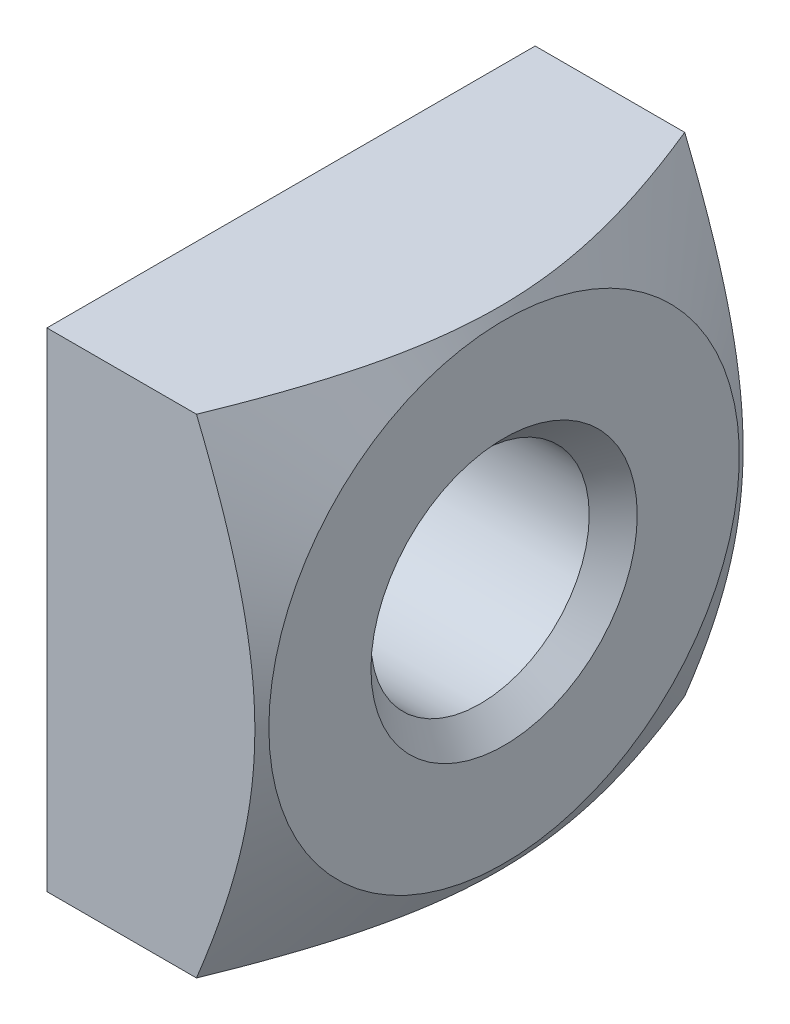
SolidWorks part; units mm, degrees
ref_plane "Front Plane" through (0, 0, 0) normal (0, 0, 1) x (1, 0, 0)
ref_plane "Top Plane" through (0, 0, 0) normal (0, 1, 0) x (1, 0, 0)
ref_plane "Right Plane" through (0, 0, 0) normal (1, 0, 0) x (0, 0, -1)
ref_plane "Plane1" through (0, 0, 0) normal (0, 0, 1) x (1, 0, 0)
sketch "Sketch1" plane through (0, 0, 0) normal (0, 0, 1) x (1, 0, 0)
  line L0 (0, 0) -> (0, 3.9)
  line L1 (0, 3.9) -> (1.6783, 3.9)
  line L2 (1.6783, 3.9) -> (2.4, 2.65)
  line L3 (2.4, 2.65) -> (2.4, 0)
  line L4 (2.4, 0) -> (0, 0)
  line L5 (2.4, 0) -> (0, 0) construction
revolve "Revolve1" add sketch "Sketch1" angle 360 about L5
ref_plane "Plane2" through (0, 0, 0) normal (1, 0, 0) x (0, 0, -1)
sketch "Sketch2" plane through (0, 0, 0) normal (1, 0, 0) x (0, 0, -1)
  line L0 (-2.75, 2.75) -> (-2.75, -2.75)
  line L1 (-2.75, -2.75) -> (2.75, -2.75)
  line L2 (2.75, -2.75) -> (2.75, 2.75)
  line L3 (2.75, 2.75) -> (-2.75, 2.75)
  circle A0 centre (0, 0) radius 5
extrude "Cut-Extrude1" cut sketch "Sketch2" along normal blind 6
ref_plane "Plane3" through (0, 0, 0) normal (0, 0, 1) x (1, 0, 0)
sketch "Sketch3" plane through (0, 0, 0) normal (0, 0, 1) x (1, 0, 0)
  line L0 (0, 0) -> (0, 1.5)
  line L1 (0, 1.5) -> (0.2705, 1.2295)
  line L2 (0.2705, 1.2295) -> (2.1295, 1.2295)
  line L3 (2.1295, 1.2295) -> (2.4, 1.5)
  line L4 (2.4, 1.5) -> (2.4, 0)
  line L5 (2.4, 0) -> (0, 0)
  line L6 (2.4, 0) -> (0, 0) construction
revolve "Cut-Revolve1" cut sketch "Sketch3" angle 360 about L6
